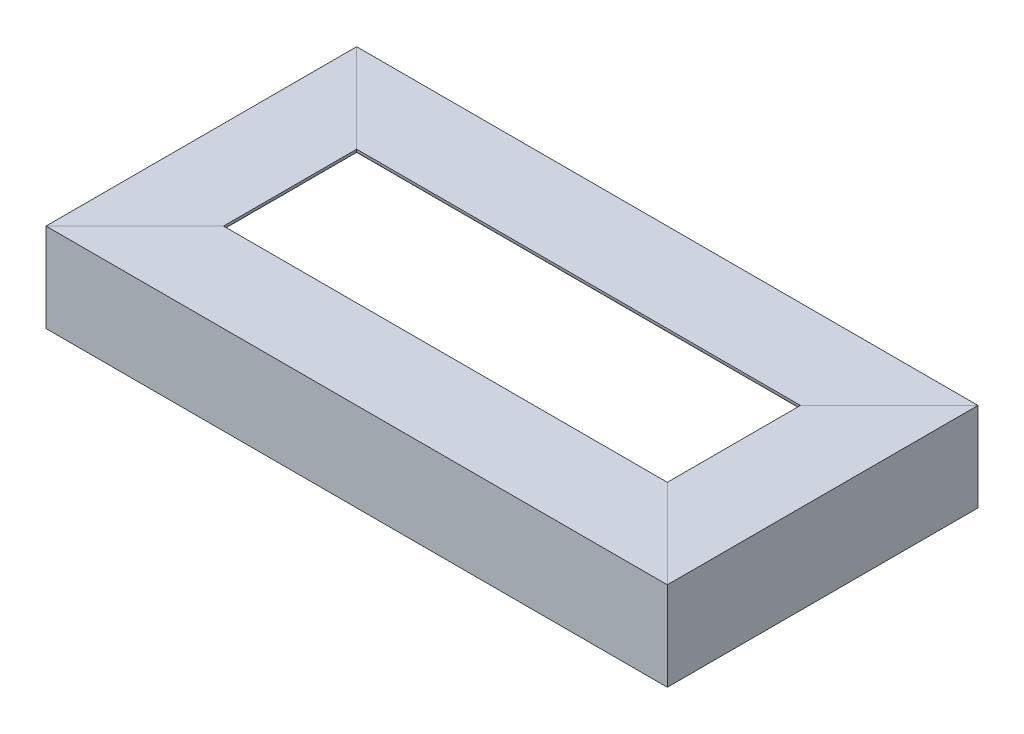
SolidWorks part; units mm, degrees
ref_plane "Front Plane" through (0, 0, 0) normal (0, 0, 1) x (1, 0, 0)
ref_plane "Top Plane" through (0, 0, 0) normal (0, 1, 0) x (1, 0, 0)
ref_plane "Right Plane" through (0, 0, 0) normal (1, 0, 0) x (0, 0, -1)
sketch3d "3DSketch2"
  line L1 (-140, 0, 70) -> (-140, 0, -70)
  line L2 (-140, 0, 70) -> (140, 0, 70)
  line L3 (140, 0, 70) -> (140, 0, -70)
  line L4 (-140, 0, -70) -> (140, 0, -70)
  line L5 (-140, 0, 70) -> (140, 0, -70) construction
  line L6 (140, 0, 70) -> (-140, 0, -70) construction
  point P0 (0, 0, 0)
  dimension "D1" = 140
  dimension "D2" = 280
other "Iron V40X40X3(1)"
ref_plane "Plane1" through (-140, 0, 70) normal (0, 0, -1) x (1, 0, 0)
sketch "Sketch1" plane through (-140, 0, 70) normal (0, 0, -1) x (1, 0, 0)
  line L0 (0, 0) -> (0, 40)
  line L1 (0, 20) -> (3, 20) construction
  line L2 (3, 37) -> (3, 6.5)
  line L3 (6.5, 3) -> (37, 3)
  line L4 (20, 3) -> (20, 0) construction
  line L5 (40, 0) -> (0, 0)
  arc A0 (40, 0) -> (37, 3) centre (37, 0) ccw
  arc A1 (0, 40) -> (3, 37) centre (0, 37) cw
  arc A2 (6.5, 3) -> (3, 6.5) centre (6.5, 6.5) cw
  point P10 (20, 0)
  point P14 (0, 20)
  point P15 (3, 20)
  point P16 (20, 3)
  point P17 (3, 40)
  point P18 (40, 3)
  point P21 (0, 0)
  dimension "D2" = 3
  dimension "D3" = 40
  dimension "Radius_1" = 3.5
  dimension "D1" = 3
